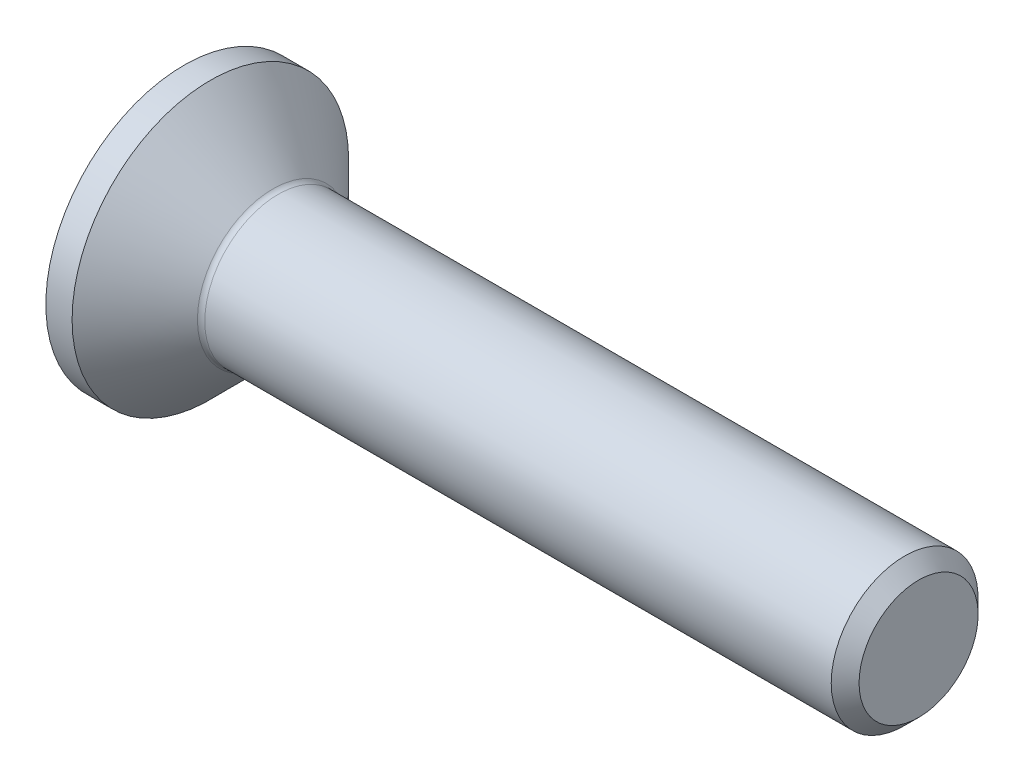
SolidWorks part; units mm, degrees
ref_plane "Front" through (0, 0, 0) normal (0, 0, 1) x (1, 0, 0)
ref_plane "Top" through (0, 0, 0) normal (0, 1, 0) x (1, 0, 0)
ref_plane "Right" through (0, 0, 0) normal (1, 0, 0) x (0, 0, -1)
sketch "Sketch1" plane through (0, 0, 0) normal (0, 0, 1) x (1, 0, 0)
  line L0 (0, 0) -> (0, 4.48)
  line L1 (0, 4.48) -> (2.48, 2)
  line L2 (2.48, 2) -> (20, 2)
  line L3 (20, 2) -> (20, 0)
  line L4 (20, 0) -> (0, 0)
  line L5 (-0.5871, 0) -> (5.4927, 0) construction
  dimension "l" = 20
  dimension "k" = 2.48
  dimension "d" = 4
  dimension "D1" = 45
revolve "Base" add sketch "Sketch1" angle 360 about L5
cosmetic thread "ThreadCosmetic1" parameters "b"=17.5, "D2"=3.242
sketch "Sketch2" plane through (0, 0, 0) normal (1, 0, 0) x (0, 0, -1)
  line L1 (1.4434, 0) -> (0.7217, 1.25)
  line L2 (0.7217, 1.25) -> (-0.7217, 1.25)
  line L3 (-0.7217, 1.25) -> (-1.4434, 0)
  line L4 (-1.4434, 0) -> (-0.7217, -1.25)
  line L5 (-0.7217, -1.25) -> (0.7217, -1.25)
  line L6 (0.7217, -1.25) -> (1.4434, 0)
  circle A0 centre (0, 0) radius 1.25 construction
  dimension "s" = 2.5
extrude "HexagonSocket" cut sketch "Sketch2" along normal blind 1.5
sketch "Sketch3" plane through (0, 0, 0) normal (0, 0, 1) x (1, 0, 0)
  line L0 (-0.4391, 0) -> (4.425, 0) construction
  line L1 (1.5, 0) -> (1.5, -1.25) construction
  line L2 (1.5, 1.25) -> (2.2217, 0)
  line L3 (2.2217, 0) -> (1.5, -1.25) construction
  line L4 (1.5, 1.25) -> (1.5, 0)
  line L5 (1.5, 0) -> (2.2217, 0)
  line L7 (1.5, 1.25) -> (1.5, 0) construction
  dimension "D1" = 120
revolve "Cut-Revolve1" cut sketch "Sketch3" angle 360 about L0
fillet "HeadFillet" radius 0.2 1 edges at (2.48, 0, 2)
chamfer "Chamfer" distance 0.379 angle 45 1 edges at (20, 0, 2)
sketch "Sketch4" plane through (0, 0, 0) normal (0, 1, 0) x (1, 0, 0)
  line L0 (11.8531, 0) -> (-2.694, 0) construction
  line L1 (-2, 8.765) -> (3, 8.765)
  line L2 (-2, 8.765) -> (-2, 3.765)
  line L3 (-2, 3.765) -> (3, 3.765)
  line L4 (3, 8.765) -> (3, 3.765)
  line L5 (0, 4.48) -> (0, -4.48) construction
  dimension "dk" = 7.53
  dimension "D2" = 2
  dimension "D3" = 5
  dimension "D4" = 5
revolve "Cut-Revolve2" cut sketch "Sketch4" angle 360 about L0
sketch "Sketch5" plane through (0, 0, 0) normal (0, 0, 1) x (1, 0, 0)
  line L0 (19.621, 1.6718) -> (19.8105, 2)
  line L1 (19.8105, 2) -> (19.8105, 2.379)
  line L2 (19.8105, 2.379) -> (19.4315, 2.379)
  line L3 (19.4315, 2.379) -> (19.4315, 2)
  line L4 (19.4315, 2) -> (19.621, 1.6718)
  line L5 (0, 0) -> (10.6885, 0) construction
  line L6 (19.621, 2) -> (19.621, -2) construction
  dimension "D1" = 4
  dimension "D2" = 0.379
revolve "Cut-Revolve10" [suppressed] cut sketch "Sketch5" angle 360 about L5
pattern_linear "LPattern10" [suppressed] count 38 spacing 0.4548 along (1, 0, 0)
equation "\"D1@Chamfer\" = (  \"d@Sketch1\" - \"D2@ThreadCosmetic1\" )  / 2"
equation "\"D1@Sketch5\" = \"d@Sketch1\""
equation "\"D2@Sketch5\" =  ( \"d@Sketch1\" - \"D2@ThreadCosmetic1\" )  / 2"
equation "\"D3@LPattern10\" = \"D2@Sketch5\" * 1.2"
equation "\"D1@LPattern10\" = \"b@ThreadCosmetic1\" / \"D3@LPattern10\""
